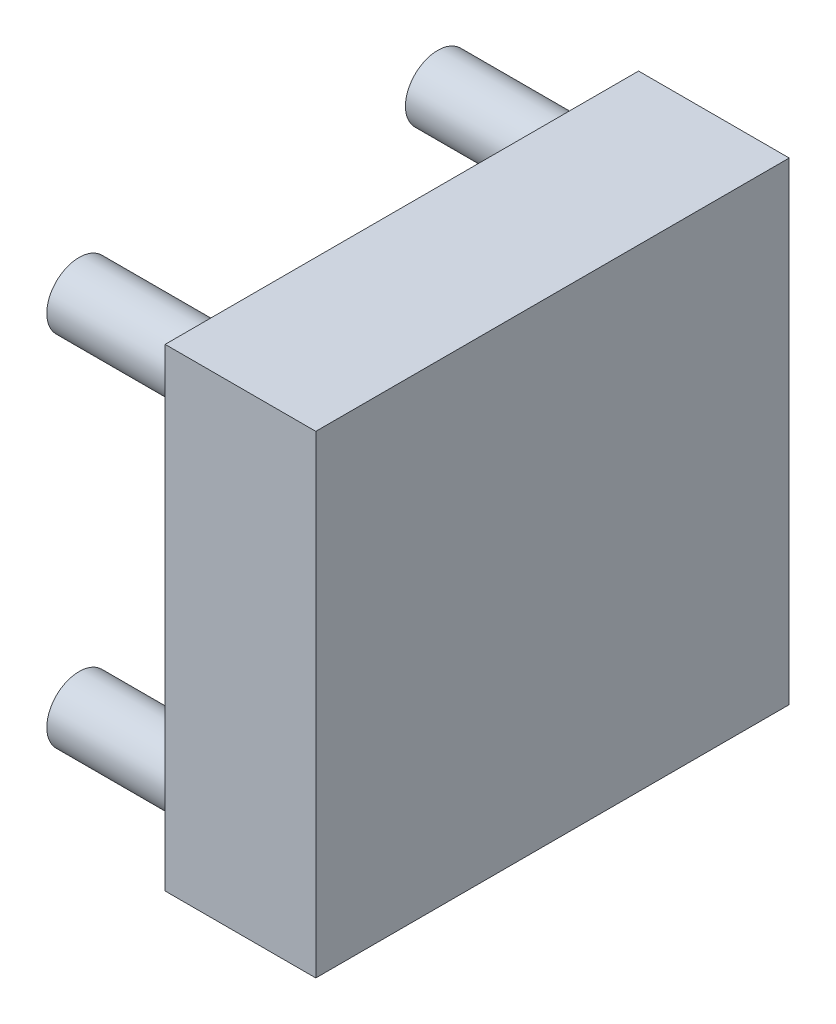
SolidWorks part; units mm, degrees
ref_plane "Front Plane" through (0, 0, 0) normal (0, 0, 1) x (1, 0, 0)
ref_plane "Top Plane" through (0, 0, 0) normal (0, 1, 0) x (1, 0, 0)
ref_plane "Right Plane" through (0, 0, 0) normal (1, 0, 0) x (0, 0, -1)
sketch "Sketch1" plane through (0, 0, 0) normal (1, 0, 0) x (0, 0, -1)
  line L1 (-16.5, -16.5) -> (16.5, -16.5)
  line L2 (-16.5, -16.5) -> (-16.5, 16.5)
  line L3 (-16.5, 16.5) -> (16.5, 16.5)
  line L4 (16.5, -16.5) -> (16.5, 16.5)
  line L5 (-16.5, -16.5) -> (16.5, 16.5) construction
  line L6 (-16.5, 16.5) -> (16.5, -16.5) construction
  point P0 (0, 0)
  dimension "D1" = 33
extrude "Boss-Extrude1" add sketch "Sketch1" along normal blind 10.5
sketch "Sketch2" plane through (0, 0, 0) normal (-1, 0, 0) x (0, 0, 1)
  line L1 (-12.5, -12.5) -> (12.5, -12.5) construction
  line L2 (-12.5, -12.5) -> (-12.5, 12.5) construction
  line L3 (-12.5, 12.5) -> (12.5, 12.5) construction
  line L4 (12.5, -12.5) -> (12.5, 12.5) construction
  line L5 (-12.5, -12.5) -> (12.5, 12.5) construction
  line L6 (-12.5, 12.5) -> (12.5, -12.5) construction
  line L7 (-16.5, -16.5) -> (-16.5, 16.5) construction
  circle A0 centre (-12.5, 12.5) radius 1.5
  circle A1 centre (12.5, 12.5) radius 1.5
  circle A2 centre (12.5, -12.5) radius 1.5
  circle A3 centre (-12.5, -12.5) radius 1.5
  circle A4 centre (-12.5, 12.5) radius 2.25
  circle A5 centre (-12.5, -12.5) radius 2.25
  circle A6 centre (12.5, -12.5) radius 2.25
  circle A7 centre (12.5, 12.5) radius 2.25
  point P0 (0, 0)
  dimension "D1" = 3
  dimension "D2" = 4.5
  dimension "D3" = 4
extrude "Boss-Extrude2" add sketch "Sketch2" along normal blind 10
